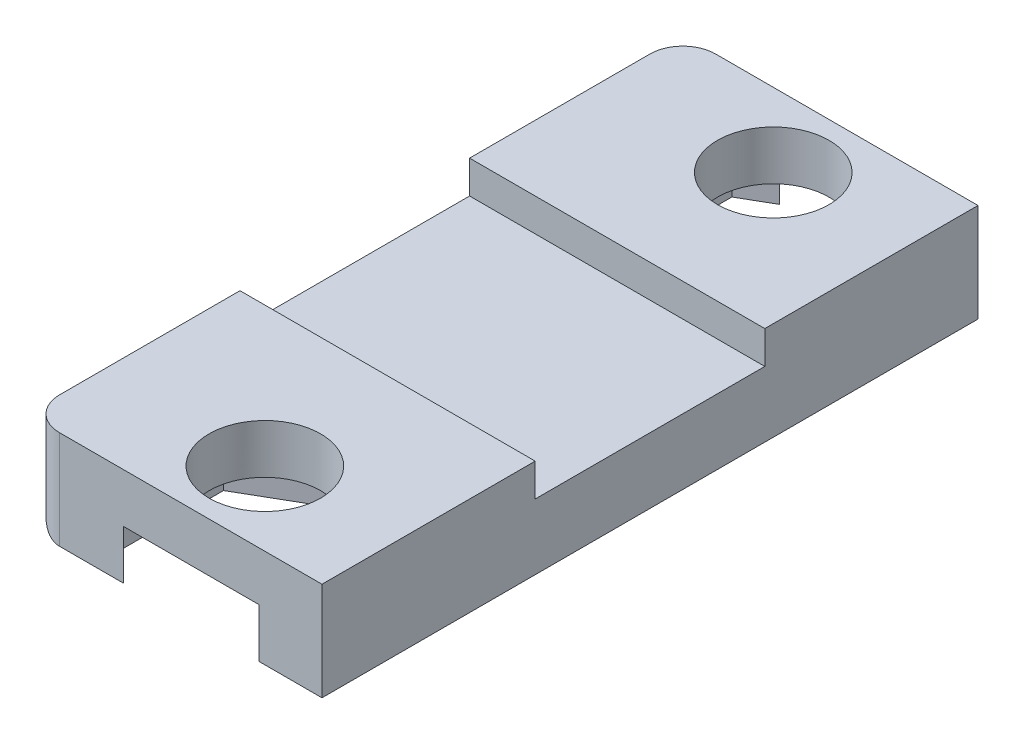
SolidWorks part; units mm, degrees
ref_plane "Alzado" through (0, 0, 0) normal (0, 0, 1) x (1, 0, 0)
ref_plane "Planta" through (0, 0, 0) normal (0, 1, 0) x (1, 0, 0)
ref_plane "Vista lateral" through (0, 0, 0) normal (1, 0, 0) x (0, 0, -1)
sketch "Croquis1" plane through (0, 0, 0) normal (0, 1, 0) x (1, 0, 0)
  line L1 (160.9544, -2) -> (169.9544, -2)
  line L2 (160.9544, -2) -> (160.9544, -22)
  line L3 (160.9544, -22) -> (169.9544, -22)
  line L4 (169.9544, -2) -> (169.9544, -22)
  circle A0 centre (165.9623, -4.25) radius 1.7
  circle A1 centre (165.9623, -19.75) radius 1.7
  dimension "D3" = 3.4
  dimension "D4" = 3.4
  dimension "D5" = 5.0079
  dimension "D6" = 2.25
  dimension "D1" = 20
  dimension "D2" = 9
  dimension "D7" = 15.5
extrude "Saliente-Extruir1" add sketch "Croquis1" against normal blind 3 separate body
sketch "Croquis2" plane through (0, -3, 0) normal (0, -1, 0) x (1, 0, 0)
  line L0 (160.9544, 2) -> (160.9544, 22) construction
  line L1 (168.9438, 21.4714) -> (165.9623, 23.1928)
  line L2 (165.9623, 23.1928) -> (162.9808, 21.4714)
  line L3 (162.9808, 21.4714) -> (162.9808, 18.0286)
  line L4 (162.9808, 18.0286) -> (165.9623, 16.3072)
  line L5 (165.9623, 16.3072) -> (168.9438, 18.0286)
  line L6 (168.9438, 18.0286) -> (168.9438, 21.4714)
  line L7 (160.9544, 12) -> (169.9544, 12) construction
  line L8 (169.9544, 22) -> (169.9544, 2) construction
  line L9 (168.9438, 5.9714) -> (168.9438, 2.5286)
  line L10 (165.9623, 7.6928) -> (168.9438, 5.9714)
  line L11 (162.9808, 5.9714) -> (165.9623, 7.6928)
  line L13 (162.9808, 2.5286) -> (162.9808, 5.9714)
  line L14 (165.9623, 0.8072) -> (162.9808, 2.5286)
  line L15 (168.9438, 2.5286) -> (165.9623, 0.8072)
  circle A0 centre (165.9623, 19.75) radius 2.9815 construction
  circle A1 centre (165.9623, 4.25) radius 2.9815 construction
extrude "Cortar-Extruir2" cut sketch "Croquis2" against normal blind 1.5
sketch "Croquis3" plane through (160.9544, 0, 0) normal (-1, 0, 0) x (0, 0, 1)
  line L0 (12, -3) -> (12, 0) construction
  line L1 (2, -3) -> (22, -3) construction
  line L2 (2, 0) -> (22, 0) construction
  line L4 (8.5, -1) -> (15.5, -1)
  line L5 (8.5, -1) -> (8.5, 0)
  line L6 (8.5, 0) -> (15.5, 0)
  line L7 (15.5, -1) -> (15.5, 0)
  line L8 (8.5, -1) -> (15.5, 0) construction
  line L9 (8.5, 0) -> (15.5, -1) construction
  point P6 (12, -0.5)
  dimension "D1" = 7
  dimension "D2" = 1
extrude "Cortar-Extruir3" cut sketch "Croquis3" against normal up to next
fillet "Redondeo1" radius 1 3 edges at (160.9544, -1.5, 2) (160.9544, -1.5, 22) (160.9544, -3, 12)
